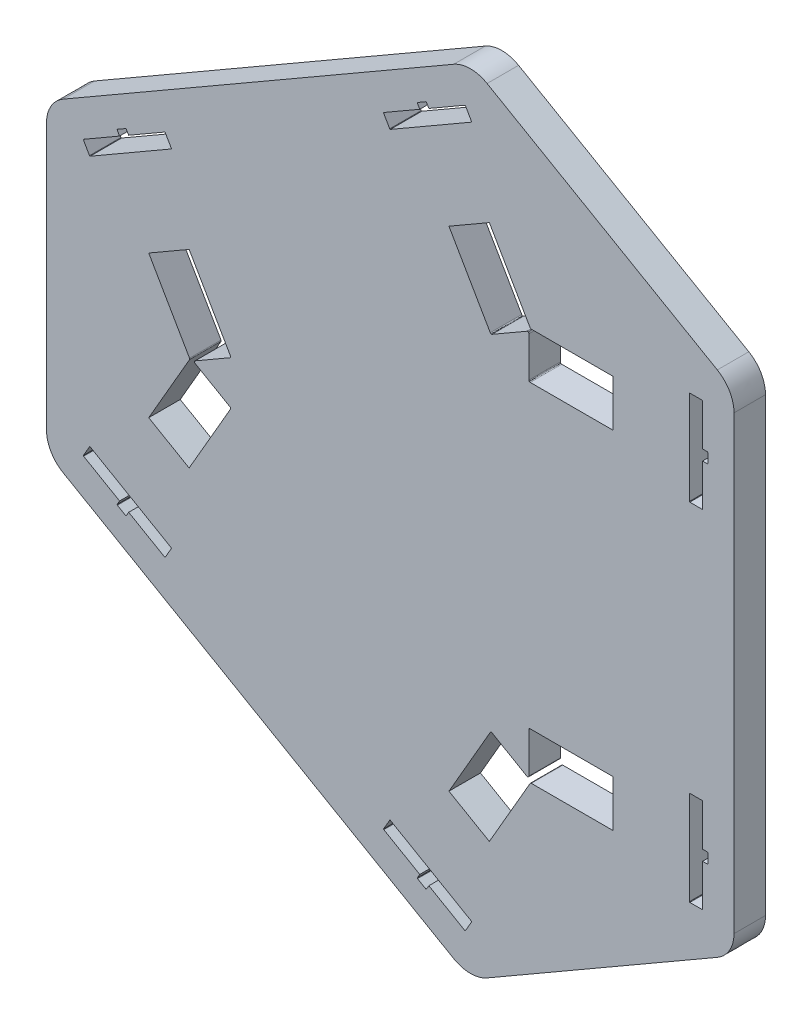
SolidWorks part; units mm, degrees
ref_plane "Alzado" through (0, 0, 0) normal (0, 0, 1) x (1, 0, 0)
ref_plane "Planta" through (0, 0, 0) normal (0, 1, 0) x (1, 0, 0)
ref_plane "Vista lateral" through (0, 0, 0) normal (1, 0, 0) x (0, 0, -1)
sketch "Model" plane through (0, 0, 0) normal (0, 0, 1) x (1, 0, 0)
  line L0 (52.0481, 135.0154) -> (53.1981, 133.0236)
  line L1 (53.1981, 133.0236) -> (52.0481, 135.0154)
  line L2 (53.1614, 132.8871) -> (37.7461, 123.9869)
  line L3 (37.7461, 123.9869) -> (53.1614, 132.8871)
  line L4 (37.6096, 124.0236) -> (36.4596, 126.0153)
  line L5 (36.4596, 126.0153) -> (37.6096, 124.0236)
  line L6 (42.9244, 131.0181) -> (44.4832, 131.918)
  line L7 (44.4832, 131.918) -> (42.9244, 131.0181)
  line L8 (36.4596, 73.9849) -> (37.6096, 75.9766)
  line L9 (37.6096, 75.9766) -> (36.4596, 73.9849)
  line L10 (37.7461, 76.0133) -> (53.1614, 67.1135)
  line L11 (53.1614, 67.1135) -> (37.7461, 76.0133)
  line L12 (53.1981, 66.9769) -> (52.0481, 64.9851)
  line L13 (52.0481, 64.9851) -> (53.1981, 66.9769)
  line L14 (44.4832, 68.0825) -> (42.9244, 68.9825)
  line L15 (42.9244, 68.9825) -> (44.4832, 68.0825)
  line L16 (110.3902, 33.9568) -> (109.2405, 31.965)
  line L17 (109.2405, 31.965) -> (110.3902, 33.9568)
  line L18 (101.6756, 35.0624) -> (100.1166, 35.9624)
  line L19 (100.1166, 35.9624) -> (101.6756, 35.0624)
  line L20 (93.652, 40.965) -> (94.802, 42.9567)
  line L21 (94.802, 42.9567) -> (93.652, 40.965)
  line L22 (94.9386, 42.9934) -> (110.3535, 34.0933)
  line L23 (110.3535, 34.0933) -> (94.9386, 42.9934)
  line L24 (155.4001, 133.9204) -> (155.4001, 132.1202)
  line L25 (155.4001, 132.1202) -> (155.4001, 133.9204)
  line L26 (154.2998, 124.0204) -> (152, 124.0204)
  line L27 (152, 124.0204) -> (154.2998, 124.0204)
  line L28 (151.8998, 124.1202) -> (151.8998, 141.9203)
  line L29 (151.8998, 141.9203) -> (151.8998, 124.1202)
  line L30 (152, 142.0202) -> (154.2998, 142.0202)
  line L31 (154.2998, 142.0202) -> (152, 142.0202)
  line L32 (121.3199, 128.8319) -> (121.3201, 136.4875)
  line L33 (121.3201, 136.4875) -> (121.3199, 128.8319)
  line L34 (120.9391, 136.7074) -> (114.309, 132.8797)
  line L35 (114.309, 132.8797) -> (120.9391, 136.7074)
  line L36 (113.3571, 26.2106) -> (157.225, 51.5377)
  line L37 (157.225, 51.5377) -> (113.3571, 26.2106)
  line L38 (160.4, 57.037) -> (160.4, 142.9631)
  line L39 (160.4, 142.9631) -> (160.4, 57.037)
  line L40 (157.225, 148.4626) -> (113.3571, 173.7896)
  line L41 (113.3571, 173.7896) -> (157.225, 148.4626)
  line L42 (107.0071, 173.7896) -> (32.5928, 130.8265)
  line L43 (32.5928, 130.8265) -> (107.0071, 173.7896)
  line L44 (29.4178, 125.3271) -> (29.4178, 74.6728)
  line L45 (29.4178, 74.6728) -> (29.4178, 125.3271)
  line L46 (32.5928, 69.1737) -> (107.0071, 26.2106)
  line L47 (107.0071, 26.2106) -> (32.5928, 69.1737)
  line L48 (101.8121, 35.099) -> (102.2622, 35.8785)
  line L49 (102.2622, 35.8785) -> (109.1036, 31.9285)
  line L50 (100.0803, 36.099) -> (100.5301, 36.8784)
  line L51 (100.5301, 36.8784) -> (93.6887, 40.8284)
  line L52 (51.9114, 64.9485) -> (45.0698, 68.8985)
  line L53 (45.0698, 68.8985) -> (44.6197, 68.1192)
  line L54 (42.8877, 69.119) -> (43.3378, 69.8983)
  line L55 (43.3378, 69.8983) -> (36.4961, 73.8483)
  line L56 (42.8877, 130.8816) -> (43.3378, 130.1019)
  line L57 (43.3378, 130.1019) -> (36.4961, 126.1519)
  line L58 (44.6197, 131.8813) -> (45.0698, 131.102)
  line L59 (45.0698, 131.102) -> (51.9114, 135.0517)
  line L60 (155.2999, 134.0202) -> (154.4, 134.0202)
  line L61 (154.4, 134.0202) -> (154.4, 141.9203)
  line L62 (155.2999, 132.0203) -> (154.4, 132.0203)
  line L63 (154.4, 132.0203) -> (154.4, 124.1202)
  line L64 (121.7786, 137.4679) -> (137.3201, 137.4676)
  line L65 (113.7878, 151.0538) -> (121.5586, 137.5949)
  line L66 (137.3199, 128.5783) -> (121.5741, 128.5779)
  line L67 (137.3199, 128.5783) -> (137.3201, 137.4676)
  line L68 (113.7878, 151.0538) -> (106.0889, 146.609)
  line L69 (106.0889, 146.609) -> (113.9622, 132.9726)
  line L70 (114.3089, 67.1204) -> (120.9388, 63.2925)
  line L71 (120.9388, 63.2925) -> (114.3089, 67.1204)
  line L72 (121.3198, 63.5125) -> (121.3199, 71.1682)
  line L73 (121.3199, 71.1682) -> (121.3198, 63.5125)
  line L74 (121.5586, 62.4052) -> (113.7876, 48.946)
  line L75 (137.3197, 62.5325) -> (121.7786, 62.5322)
  line L76 (106.0893, 53.3908) -> (113.9619, 67.0273)
  line L77 (137.3199, 71.4223) -> (121.5738, 71.422)
  line L78 (106.0893, 53.3908) -> (113.7876, 48.946)
  line L79 (137.3197, 62.5325) -> (137.3199, 71.4223)
  line L80 (64.3709, 104.0478) -> (57.7409, 100.2201)
  line L81 (57.7409, 100.2201) -> (64.3709, 104.0478)
  line L82 (57.7409, 99.7802) -> (64.3709, 95.9522)
  line L83 (64.3709, 95.9522) -> (57.7409, 99.7802)
  line L84 (56.6626, 100.127) -> (48.8921, 113.5865)
  line L85 (48.8923, 86.4138) -> (56.6626, 99.873)
  line L86 (56.5906, 118.031) -> (64.4638, 104.3949)
  line L87 (56.591, 81.9688) -> (64.4638, 95.6055)
  line L88 (56.5906, 118.031) -> (48.8921, 113.5865)
  line L89 (48.8923, 86.4138) -> (56.591, 81.9688)
  line L90 (155.4001, 67.8804) -> (155.4001, 66.0802)
  line L91 (155.4001, 66.0802) -> (155.4001, 67.8804)
  line L92 (154.2998, 57.9804) -> (152, 57.9804)
  line L93 (152, 57.9804) -> (154.2998, 57.9804)
  line L94 (151.8998, 58.0802) -> (151.8998, 75.8803)
  line L95 (151.8998, 75.8803) -> (151.8998, 58.0802)
  line L96 (152, 75.9802) -> (154.2998, 75.9802)
  line L97 (154.2998, 75.9802) -> (152, 75.9802)
  line L98 (155.2999, 67.9802) -> (154.4, 67.9802)
  line L99 (154.4, 67.9802) -> (154.4, 75.8803)
  line L100 (155.2999, 65.9803) -> (154.4, 65.9803)
  line L101 (154.4, 65.9803) -> (154.4, 58.0802)
  line L102 (94.8019, 157.0436) -> (93.6519, 159.0353)
  line L103 (93.6519, 159.0353) -> (94.8019, 157.0436)
  line L104 (109.2404, 168.0354) -> (110.3904, 166.0436)
  line L105 (110.3904, 166.0436) -> (109.2404, 168.0354)
  line L106 (110.3537, 165.9071) -> (94.9384, 157.0069)
  line L107 (94.9384, 157.0069) -> (110.3537, 165.9071)
  line L108 (100.1167, 164.0381) -> (101.6755, 164.938)
  line L109 (101.6755, 164.938) -> (100.1167, 164.0381)
  line L110 (100.08, 163.9016) -> (100.5301, 163.1219)
  line L111 (100.5301, 163.1219) -> (93.6884, 159.1719)
  line L112 (101.8121, 164.9013) -> (102.2621, 164.122)
  line L113 (102.2621, 164.122) -> (109.1037, 168.0717)
  spline S0 degree 3 poles (51.9114, 135.0517) (51.9344, 135.0652) (51.9617, 135.0687) (51.9872, 135.062) knots 0 0 0 0 1 1 1 1
  spline S1 degree 3 poles (51.9872, 135.062) (52.0128, 135.0549) (52.0347, 135.0383) (52.0481, 135.0154) knots 0 0 0 0 1 1 1 1
  spline S2 degree 3 poles (53.1981, 133.0236) (53.2113, 133.0007) (53.2149, 132.9732) (53.208, 132.9478) knots 0 0 0 0 1 1 1 1
  spline S3 degree 3 poles (53.208, 132.9478) (53.2012, 132.922) (53.1843, 132.9002) (53.1614, 132.8871) knots 0 0 0 0 1 1 1 1
  spline S4 degree 3 poles (37.7461, 123.9869) (37.7232, 123.9735) (37.6959, 123.9699) (37.6703, 123.977) knots 0 0 0 0 1 1 1 1
  spline S5 degree 3 poles (37.6703, 123.977) (37.6447, 123.9837) (37.6228, 124.0006) (37.6096, 124.0236) knots 0 0 0 0 1 1 1 1
  spline S6 degree 3 poles (36.4596, 126.0153) (36.4463, 126.0383) (36.4427, 126.0654) (36.4495, 126.0912) knots 0 0 0 0 1 1 1 1
  spline S7 degree 3 poles (36.4495, 126.0912) (36.4564, 126.1169) (36.4732, 126.1388) (36.4961, 126.1519) knots 0 0 0 0 1 1 1 1
  spline S8 degree 3 poles (42.8877, 130.8816) (42.8745, 130.9041) (42.8709, 130.9317) (42.8778, 130.9571) knots 0 0 0 0 1 1 1 1
  spline S9 degree 3 poles (42.8778, 130.9571) (42.8847, 130.9828) (42.9015, 131.0047) (42.9244, 131.0181) knots 0 0 0 0 1 1 1 1
  spline S10 degree 3 poles (44.4832, 131.918) (44.5061, 131.9311) (44.5333, 131.9346) (44.559, 131.9279) knots 0 0 0 0 1 1 1 1
  spline S11 degree 3 poles (44.559, 131.9279) (44.5846, 131.9212) (44.6065, 131.9043) (44.6197, 131.8813) knots 0 0 0 0 1 1 1 1
  spline S12 degree 3 poles (42.9244, 68.9825) (42.9015, 68.9955) (42.8847, 69.0174) (42.8778, 69.0431) knots 0 0 0 0 1 1 1 1
  spline S13 degree 3 poles (42.8778, 69.0431) (42.8709, 69.0685) (42.8745, 69.0961) (42.8877, 69.119) knots 0 0 0 0 1 1 1 1
  spline S14 degree 3 poles (36.4961, 73.8483) (36.4732, 73.8617) (36.4564, 73.8833) (36.4495, 73.909) knots 0 0 0 0 1 1 1 1
  spline S15 degree 3 poles (36.4495, 73.909) (36.4427, 73.9348) (36.4463, 73.9619) (36.4596, 73.9849) knots 0 0 0 0 1 1 1 1
  spline S16 degree 3 poles (37.6096, 75.9766) (37.6228, 75.9999) (37.6447, 76.0165) (37.6702, 76.0232) knots 0 0 0 0 1 1 1 1
  spline S17 degree 3 poles (37.6702, 76.0232) (37.6958, 76.0303) (37.7232, 76.0267) (37.7461, 76.0133) knots 0 0 0 0 1 1 1 1
  spline S18 degree 3 poles (53.1614, 67.1135) (53.1844, 67.1004) (53.2011, 67.0785) (53.208, 67.0528) knots 0 0 0 0 1 1 1 1
  spline S19 degree 3 poles (53.208, 67.0528) (53.2149, 67.0274) (53.2113, 66.9999) (53.1981, 66.9769) knots 0 0 0 0 1 1 1 1
  spline S20 degree 3 poles (52.0481, 64.9851) (52.0348, 64.9619) (52.0129, 64.9453) (51.9873, 64.9386) knots 0 0 0 0 1 1 1 1
  spline S21 degree 3 poles (51.9873, 64.9386) (51.9618, 64.9315) (51.9344, 64.935) (51.9114, 64.9485) knots 0 0 0 0 1 1 1 1
  spline S22 degree 3 poles (44.6197, 68.1192) (44.6067, 68.0959) (44.5847, 68.0794) (44.5591, 68.0723) knots 0 0 0 0 1 1 1 1
  spline S23 degree 3 poles (44.5591, 68.0723) (44.5335, 68.0656) (44.5062, 68.0691) (44.4832, 68.0825) knots 0 0 0 0 1 1 1 1
  spline S24 degree 3 poles (110.3535, 34.0933) (110.3768, 34.0803) (110.3934, 34.0583) (110.4005, 34.0329) knots 0 0 0 0 1 1 1 1
  spline S25 degree 3 poles (110.4005, 34.0329) (110.4072, 34.0072) (110.4036, 33.9798) (110.3902, 33.9568) knots 0 0 0 0 1 1 1 1
  spline S26 degree 3 poles (109.2405, 31.965) (109.2271, 31.942) (109.2052, 31.9253) (109.1798, 31.9184) knots 0 0 0 0 1 1 1 1
  spline S27 degree 3 poles (109.1798, 31.9184) (109.1541, 31.9115) (109.1266, 31.9151) (109.1036, 31.9285) knots 0 0 0 0 1 1 1 1
  spline S28 degree 3 poles (101.8121, 35.099) (101.799, 35.076) (101.7772, 35.0592) (101.7514, 35.0525) knots 0 0 0 0 1 1 1 1
  spline S29 degree 3 poles (101.7514, 35.0525) (101.726, 35.0455) (101.6985, 35.0492) (101.6756, 35.0624) knots 0 0 0 0 1 1 1 1
  spline S30 degree 3 poles (100.1166, 35.9624) (100.0937, 35.9756) (100.0771, 35.9974) (100.0701, 36.023) knots 0 0 0 0 1 1 1 1
  spline S31 degree 3 poles (100.0701, 36.023) (100.0634, 36.0487) (100.0669, 36.076) (100.0803, 36.099) knots 0 0 0 0 1 1 1 1
  spline S32 degree 3 poles (93.6887, 40.8284) (93.6654, 40.8416) (93.6488, 40.8634) (93.6421, 40.889) knots 0 0 0 0 1 1 1 1
  spline S33 degree 3 poles (93.6421, 40.889) (93.635, 40.9147) (93.6386, 40.9421) (93.652, 40.965) knots 0 0 0 0 1 1 1 1
  spline S34 degree 3 poles (94.802, 42.9567) (94.8151, 42.9798) (94.837, 42.9966) (94.8624, 43.0033) knots 0 0 0 0 1 1 1 1
  spline S35 degree 3 poles (94.8624, 43.0033) (94.8881, 43.0104) (94.9156, 43.0067) (94.9386, 42.9934) knots 0 0 0 0 1 1 1 1
  spline S36 degree 3 poles (154.2998, 142.0202) (154.3266, 142.0202) (154.352, 142.0096) (154.3707, 141.9909) knots 0 0 0 0 1 1 1 1
  spline S37 degree 3 poles (154.3707, 141.9909) (154.3894, 141.9722) (154.4, 141.9468) (154.4, 141.9203) knots 0 0 0 0 1 1 1 1
  spline S38 degree 3 poles (155.2999, 134.0202) (155.3263, 134.0202) (155.3517, 134.0096) (155.3708, 133.9909) knots 0 0 0 0 1 1 1 1
  spline S39 degree 3 poles (155.3708, 133.9909) (155.3895, 133.9722) (155.4001, 133.9468) (155.4001, 133.9204) knots 0 0 0 0 1 1 1 1
  spline S40 degree 3 poles (155.4001, 132.1202) (155.4001, 132.0937) (155.3895, 132.0683) (155.3708, 132.0496) knots 0 0 0 0 1 1 1 1
  spline S41 degree 3 poles (155.3708, 132.0496) (155.3521, 132.0306) (155.3263, 132.0203) (155.2999, 132.0203) knots 0 0 0 0 1 1 1 1
  spline S42 degree 3 poles (154.4, 124.1202) (154.4, 124.0938) (154.3894, 124.0684) (154.3707, 124.0493) knots 0 0 0 0 1 1 1 1
  spline S43 degree 3 poles (154.3707, 124.0493) (154.352, 124.0306) (154.3266, 124.0204) (154.2998, 124.0204) knots 0 0 0 0 1 1 1 1
  spline S44 degree 3 poles (152, 124.0204) (151.9735, 124.02) (151.9481, 124.0306) (151.9291, 124.0493) knots 0 0 0 0 1 1 1 1
  spline S45 degree 3 poles (151.9291, 124.0493) (151.9104, 124.068) (151.8998, 124.0938) (151.8998, 124.1202) knots 0 0 0 0 1 1 1 1
  spline S46 degree 3 poles (151.8998, 141.9203) (151.8998, 141.9468) (151.9104, 141.9722) (151.9291, 141.9909) knots 0 0 0 0 1 1 1 1
  spline S47 degree 3 poles (151.9291, 141.9909) (151.9481, 142.0096) (151.9735, 142.0202) (152, 142.0202) knots 0 0 0 0 1 1 1 1
  spline S48 degree 3 poles (121.5586, 137.5949) (121.6041, 137.5163) (121.6881, 137.4678) (121.7786, 137.4679) knots 0 0 0 0 1 1 1 1
  spline S49 degree 3 poles (121.5741, 128.5779) (121.5068, 128.5778) (121.442, 128.6045) (121.3945, 128.6521) knots 0 0 0 0 1 1 1 1
  spline S50 degree 3 poles (121.3945, 128.6521) (121.3467, 128.6998) (121.3202, 128.7646) (121.3199, 128.8319) knots 0 0 0 0 1 1 1 1
  spline S51 degree 3 poles (121.3201, 136.4875) (121.32, 136.5783) (121.2711, 136.6623) (121.1925, 136.7074) knots 0 0 0 0 1 1 1 1
  spline S52 degree 3 poles (121.1925, 136.7074) (121.1136, 136.7528) (121.0175, 136.753) (120.9391, 136.7074) knots 0 0 0 0 1 1 1 1
  spline S53 degree 3 poles (114.309, 132.8797) (114.2508, 132.8459) (114.1815, 132.8367) (114.1163, 132.8542) knots 0 0 0 0 1 1 1 1
  spline S54 degree 3 poles (114.1163, 132.8542) (114.0513, 132.8715) (113.9957, 132.9143) (113.9622, 132.9726) knots 0 0 0 0 1 1 1 1
  spline S55 degree 3 poles (157.225, 51.5377) (159.1903, 52.6729) (160.4004, 54.7675) (160.4, 57.037) knots 0 0 0 0 1 1 1 1
  spline S56 degree 3 poles (160.4, 142.9631) (160.3996, 145.2326) (159.1907, 147.3284) (157.225, 148.4626) knots 0 0 0 0 1 1 1 1
  spline S57 degree 3 poles (113.3571, 173.7896) (111.3914, 174.9238) (108.9721, 174.9248) (107.0071, 173.7896) knots 0 0 0 0 1 1 1 1
  spline S58 degree 3 poles (32.5928, 130.8265) (30.6277, 129.6913) (29.4174, 127.5965) (29.4178, 125.3271) knots 0 0 0 0 1 1 1 1
  spline S59 degree 3 poles (29.4178, 74.6728) (29.4182, 72.4034) (30.6272, 70.3079) (32.5928, 69.1737) knots 0 0 0 0 1 1 1 1
  spline S60 degree 3 poles (107.0071, 26.2106) (108.9728, 25.0763) (111.3918, 25.0753) (113.3571, 26.2106) knots 0 0 0 0 1 1 1 1
  spline S61 degree 3 poles (121.7786, 62.5322) (121.6878, 62.5322) (121.6037, 62.4837) (121.5586, 62.4052) knots 0 0 0 0 1 1 1 1
  spline S62 degree 3 poles (113.9619, 67.0273) (113.9954, 67.0857) (114.051, 67.1284) (114.1159, 67.1457) knots 0 0 0 0 1 1 1 1
  spline S63 degree 3 poles (114.1159, 67.1457) (114.1811, 67.1633) (114.2505, 67.1539) (114.3089, 67.1204) knots 0 0 0 0 1 1 1 1
  spline S64 degree 3 poles (120.9388, 63.2925) (121.0175, 63.2472) (121.1147, 63.2475) (121.1931, 63.2931) knots 0 0 0 0 1 1 1 1
  spline S65 degree 3 poles (121.1931, 63.2931) (121.2718, 63.3387) (121.32, 63.4218) (121.3198, 63.5125) knots 0 0 0 0 1 1 1 1
  spline S66 degree 3 poles (121.3199, 71.1682) (121.3198, 71.2355) (121.3464, 71.3) (121.3942, 71.3478) knots 0 0 0 0 1 1 1 1
  spline S67 degree 3 poles (121.3942, 71.3478) (121.4417, 71.3954) (121.5065, 71.4222) (121.5738, 71.422) knots 0 0 0 0 1 1 1 1
  spline S68 degree 3 poles (56.6626, 99.873) (56.708, 99.9517) (56.708, 100.0487) (56.6626, 100.127) knots 0 0 0 0 1 1 1 1
  spline S69 degree 3 poles (64.4638, 104.3949) (64.4976, 104.3367) (64.5068, 104.2672) (64.4893, 104.2023) knots 0 0 0 0 1 1 1 1
  spline S70 degree 3 poles (64.4893, 104.2023) (64.472, 104.137) (64.4291, 104.0816) (64.3709, 104.0478) knots 0 0 0 0 1 1 1 1
  spline S71 degree 3 poles (57.7409, 100.2201) (57.6624, 100.1746) (57.614, 100.0903) (57.6143, 99.9997) knots 0 0 0 0 1 1 1 1
  spline S72 degree 3 poles (57.6143, 99.9997) (57.6144, 99.9086) (57.6623, 99.8254) (57.7409, 99.7802) knots 0 0 0 0 1 1 1 1
  spline S73 degree 3 poles (64.3709, 95.9522) (64.4293, 95.9187) (64.4718, 95.8633) (64.4893, 95.7981) knots 0 0 0 0 1 1 1 1
  spline S74 degree 3 poles (64.4893, 95.7981) (64.5068, 95.7332) (64.4976, 95.6637) (64.4638, 95.6055) knots 0 0 0 0 1 1 1 1
  spline S75 degree 3 poles (154.2998, 75.9802) (154.3266, 75.9802) (154.352, 75.9696) (154.3707, 75.9509) knots 0 0 0 0 1 1 1 1
  spline S76 degree 3 poles (154.3707, 75.9509) (154.3894, 75.9322) (154.4, 75.9068) (154.4, 75.8803) knots 0 0 0 0 1 1 1 1
  spline S77 degree 3 poles (155.2999, 67.9802) (155.3263, 67.9802) (155.3517, 67.9696) (155.3708, 67.9509) knots 0 0 0 0 1 1 1 1
  spline S78 degree 3 poles (155.3708, 67.9509) (155.3895, 67.9322) (155.4001, 67.9068) (155.4001, 67.8804) knots 0 0 0 0 1 1 1 1
  spline S79 degree 3 poles (155.4001, 66.0802) (155.4001, 66.0537) (155.3895, 66.0283) (155.3708, 66.0096) knots 0 0 0 0 1 1 1 1
  spline S80 degree 3 poles (155.3708, 66.0096) (155.3521, 65.9906) (155.3263, 65.9803) (155.2999, 65.9803) knots 0 0 0 0 1 1 1 1
  spline S81 degree 3 poles (154.4, 58.0802) (154.4, 58.0538) (154.3894, 58.0284) (154.3707, 58.0093) knots 0 0 0 0 1 1 1 1
  spline S82 degree 3 poles (154.3707, 58.0093) (154.352, 57.9906) (154.3266, 57.9804) (154.2998, 57.9804) knots 0 0 0 0 1 1 1 1
  spline S83 degree 3 poles (152, 57.9804) (151.9735, 57.98) (151.9481, 57.9906) (151.9291, 58.0093) knots 0 0 0 0 1 1 1 1
  spline S84 degree 3 poles (151.9291, 58.0093) (151.9104, 58.028) (151.8998, 58.0538) (151.8998, 58.0802) knots 0 0 0 0 1 1 1 1
  spline S85 degree 3 poles (151.8998, 75.8803) (151.8998, 75.9068) (151.9104, 75.9322) (151.9291, 75.9509) knots 0 0 0 0 1 1 1 1
  spline S86 degree 3 poles (151.9291, 75.9509) (151.9481, 75.9696) (151.9735, 75.9802) (152, 75.9802) knots 0 0 0 0 1 1 1 1
  spline S87 degree 3 poles (94.9384, 157.0069) (94.9155, 156.9935) (94.8883, 156.9899) (94.8626, 156.997) knots 0 0 0 0 1 1 1 1
  spline S88 degree 3 poles (94.8626, 156.997) (94.837, 157.0037) (94.8151, 157.0206) (94.8019, 157.0436) knots 0 0 0 0 1 1 1 1
  spline S89 degree 3 poles (93.6519, 159.0353) (93.6387, 159.0583) (93.6351, 159.0854) (93.6418, 159.1112) knots 0 0 0 0 1 1 1 1
  spline S90 degree 3 poles (93.6418, 159.1112) (93.6487, 159.1369) (93.6655, 159.1588) (93.6884, 159.1719) knots 0 0 0 0 1 1 1 1
  spline S91 degree 3 poles (110.3904, 166.0436) (110.4036, 166.0207) (110.4072, 165.9932) (110.4003, 165.9678) knots 0 0 0 0 1 1 1 1
  spline S92 degree 3 poles (110.4003, 165.9678) (110.3935, 165.942) (110.3766, 165.9202) (110.3537, 165.9071) knots 0 0 0 0 1 1 1 1
  spline S93 degree 3 poles (100.08, 163.9016) (100.0668, 163.9241) (100.0632, 163.9517) (100.0701, 163.9771) knots 0 0 0 0 1 1 1 1
  spline S94 degree 3 poles (100.0701, 163.9771) (100.077, 164.0028) (100.0938, 164.0247) (100.1167, 164.0381) knots 0 0 0 0 1 1 1 1
  spline S95 degree 3 poles (101.6755, 164.938) (101.6984, 164.9511) (101.7257, 164.9546) (101.7513, 164.9479) knots 0 0 0 0 1 1 1 1
  spline S96 degree 3 poles (101.7513, 164.9479) (101.7769, 164.9412) (101.7988, 164.9243) (101.8121, 164.9013) knots 0 0 0 0 1 1 1 1
  spline S97 degree 3 poles (109.1037, 168.0717) (109.1267, 168.0852) (109.154, 168.0887) (109.1795, 168.082) knots 0 0 0 0 1 1 1 1
  spline S98 degree 3 poles (109.1795, 168.082) (109.2051, 168.0749) (109.227, 168.0583) (109.2404, 168.0354) knots 0 0 0 0 1 1 1 1
extrude "Saliente-Extruir1" add sketch "Model" along normal blind 6 contours L46 S60 L36 S55 L38 S56 L40 S57 L42 S58 L44 S59 S85 S86 L96 S75 S76 L99 L98 S77 S78 L90 S79 S80 L100 L101 S81 S82 L92 S83 S84 L94 S66 S67 L77 L79 L75 S61 L74 L78 L76 S62 S63 L70 S64 S65 L72 S53
